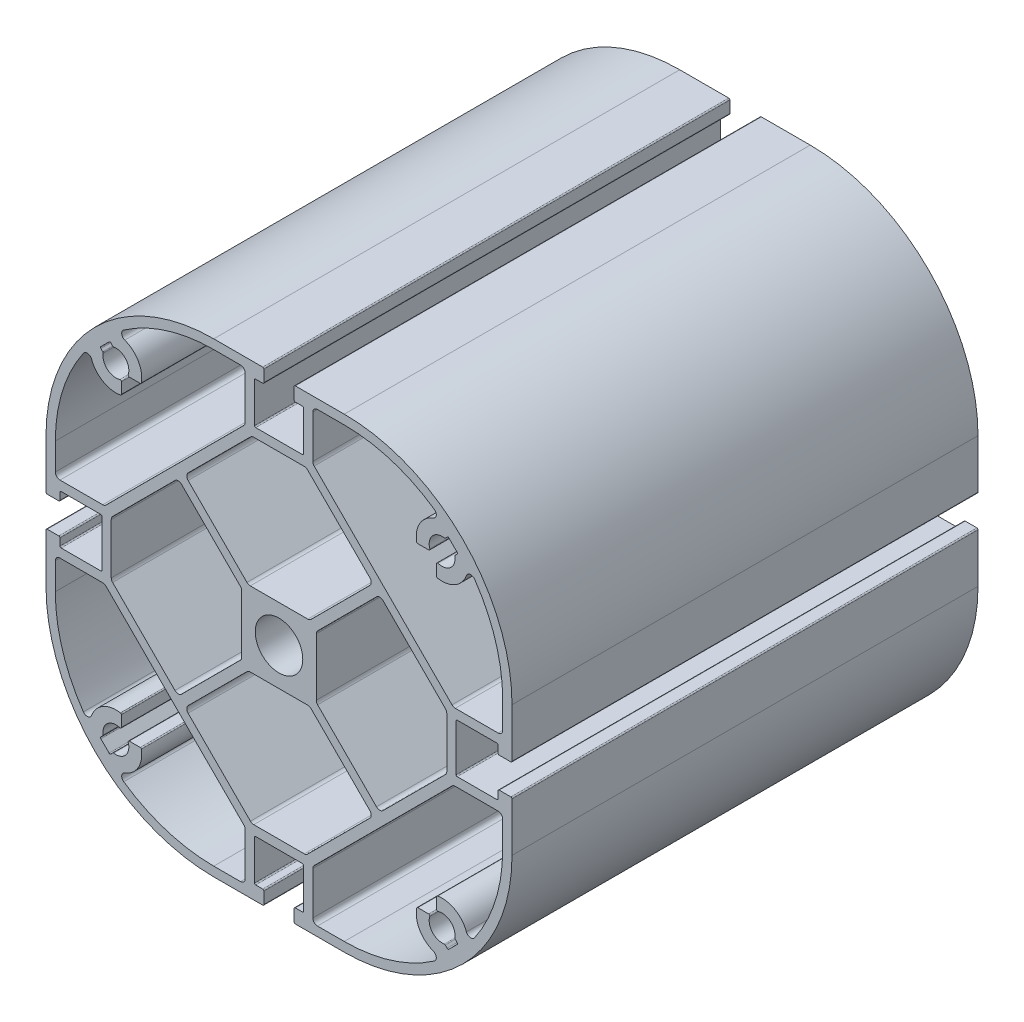
SolidWorks part; units mm, degrees
material "6061 Alaşım"
ref_plane "Ön Düzlem" through (0, 0, 0) normal (0, 0, 1) x (1, 0, 0)
ref_plane "Üst Düzlem" through (0, 0, 0) normal (0, 1, 0) x (1, 0, 0)
ref_plane "Sağ Düzlem" through (0, 0, 0) normal (1, 0, 0) x (0, 0, -1)
sketch "Çizim1" plane through (0, 0, 0) normal (0, 0, 1) x (1, 0, 0)
  line L0 (-50, 0) -> (50, 0) construction
  line L1 (50, -50) -> (-50, -50) construction
  line L2 (50, -50) -> (50, 50) construction
  line L3 (50, 50) -> (-50, 50) construction
  line L4 (-50, -50) -> (-50, 50) construction
  line L5 (50, -50) -> (-50, 50) construction
  line L6 (50, 50) -> (-50, -50) construction
  line L7 (0, 50) -> (0, -50) construction
  line L8 (3.25, 49.75) -> (3.25, 47.25)
  line L9 (3.5, 47) -> (5, 47)
  line L10 (5.25, 46.75) -> (5.25, 38.25)
  line L11 (5, 38) -> (0, 38)
  line L12 (37.1213, 7.5429) -> (7.5429, 37.1213)
  line L13 (7.25, 37.8284) -> (7.25, 47)
  line L14 (8.25, 48) -> (14, 48)
  line L15 (0, 36) -> (5.4216, 36)
  line L16 (6.1287, 35.7071) -> (19.5037, 22.3321)
  line L17 (19.5037, 20.9179) -> (6.8787, 8.2929)
  line L18 (6.1716, 8) -> (0, 8)
  line L19 (3.5, 50) -> (14, 50)
  line L20 (5.25, 38) -> (38, 5.25) construction
  line L21 (0, 8) -> (0, 5.1)
  line L22 (3.6062, 3.6062) -> (22.3321, 22.3321) construction
  line L23 (0, 38) -> (0, 36)
  line L24 (32.485, 33.8272) -> (35, 35) construction
  line L25 (35, 35) -> (33.8272, 32.485) construction
  line L26 (32.1192, 33.8272) -> (29.7809, 33.8272)
  line L28 (38.2184, 36.4506) -> (36.4506, 38.2184)
  line L29 (36.0971, 38.2184) -> (35.6841, 37.8054)
  line L30 (37.3345, 37.3345) -> (39.4558, 39.4558)
  line L31 (38.2184, 36.0971) -> (37.8054, 35.6841)
  line L32 (33.8272, 32.1192) -> (33.8272, 29.7809)
  line L33 (48, 8.25) -> (48, 14)
  line L34 (37.8284, 7.25) -> (47, 7.25)
  line L35 (8, 0) -> (5.1, 0)
  line L36 (8, 6.1716) -> (8, 0)
  line L37 (20.9179, 19.5037) -> (8.2929, 6.8787)
  line L38 (35.7071, 6.1287) -> (22.3321, 19.5037)
  line L39 (36, 0) -> (36, 5.4216)
  line L40 (38, 0) -> (36, 0)
  line L41 (38, 5) -> (38, 0)
  line L42 (46.75, 5.25) -> (38.25, 5.25)
  line L43 (47, 3.5) -> (47, 5)
  line L44 (49.75, 3.25) -> (47.25, 3.25)
  line L45 (50, 3.5) -> (50, 14)
  line L46 (0, -8) -> (0, -5.1)
  line L47 (6.1716, -8) -> (0, -8)
  line L48 (19.5037, -20.9179) -> (6.8787, -8.2929)
  line L49 (6.1287, -35.7071) -> (19.5037, -22.3321)
  line L50 (0, -36) -> (5.4216, -36)
  line L51 (0, -38) -> (0, -36)
  line L52 (5, -38) -> (0, -38)
  line L53 (5.25, -46.75) -> (5.25, -38.25)
  line L54 (3.5, -47) -> (5, -47)
  line L55 (3.25, -49.75) -> (3.25, -47.25)
  line L56 (3.5, -50) -> (14, -50)
  line L57 (50, -3.5) -> (50, -14)
  line L58 (49.75, -3.25) -> (47.25, -3.25)
  line L59 (47, -3.5) -> (47, -5)
  line L60 (46.75, -5.25) -> (38.25, -5.25)
  line L61 (38, -5) -> (38, 0)
  line L62 (38, 0) -> (36, 0)
  line L63 (36, 0) -> (36, -5.4216)
  line L64 (35.7071, -6.1287) -> (22.3321, -19.5037)
  line L65 (20.9179, -19.5037) -> (8.2929, -6.8787)
  line L66 (8, -6.1716) -> (8, 0)
  line L67 (8, 0) -> (5.1, 0)
  line L68 (36.4506, -38.2184) -> (38.2184, -36.4506)
  line L69 (38.2184, -36.0971) -> (37.8054, -35.6841)
  line L70 (33.8272, -32.1192) -> (33.8272, -29.7809)
  line L71 (48, -8.25) -> (48, -14)
  line L72 (37.8284, -7.25) -> (47, -7.25)
  line L73 (7.5429, -37.1213) -> (37.1213, -7.5429)
  line L74 (7.25, -37.8284) -> (7.25, -47)
  line L75 (8.25, -48) -> (14, -48)
  line L76 (32.1192, -33.8272) -> (29.7809, -33.8272)
  line L77 (36.0971, -38.2184) -> (35.6841, -37.8054)
  line L78 (-8, 0) -> (-5.1, 0)
  line L79 (-8, -6.1716) -> (-8, 0)
  line L80 (-20.9179, -19.5037) -> (-8.2929, -6.8787)
  line L81 (-35.7071, -6.1287) -> (-22.3321, -19.5037)
  line L82 (-36, 0) -> (-36, -5.4216)
  line L83 (-38, 0) -> (-36, 0)
  line L84 (-38, -5) -> (-38, 0)
  line L85 (-46.75, -5.25) -> (-38.25, -5.25)
  line L86 (-47, -3.5) -> (-47, -5)
  line L87 (-49.75, -3.25) -> (-47.25, -3.25)
  line L88 (-50, -3.5) -> (-50, -14)
  line L89 (-3.5, -50) -> (-14, -50)
  line L90 (-3.25, -49.75) -> (-3.25, -47.25)
  line L91 (-3.5, -47) -> (-5, -47)
  line L92 (-5.25, -46.75) -> (-5.25, -38.25)
  line L93 (-5, -38) -> (0, -38)
  line L94 (0, -38) -> (0, -36)
  line L95 (0, -36) -> (-5.4216, -36)
  line L96 (-6.1287, -35.7071) -> (-19.5037, -22.3321)
  line L97 (-19.5037, -20.9179) -> (-6.8787, -8.2929)
  line L98 (-6.1716, -8) -> (0, -8)
  line L99 (0, -8) -> (0, -5.1)
  line L100 (-38.2184, -36.4506) -> (-36.4506, -38.2184)
  line L101 (-36.0971, -38.2184) -> (-35.6841, -37.8054)
  line L102 (-32.1192, -33.8272) -> (-29.7809, -33.8272)
  line L103 (-8.25, -48) -> (-14, -48)
  line L104 (-7.25, -37.8284) -> (-7.25, -47)
  line L105 (-37.1213, -7.5429) -> (-7.5429, -37.1213)
  line L106 (-37.8284, -7.25) -> (-47, -7.25)
  line L107 (-48, -8.25) -> (-48, -14)
  line L108 (-33.8272, -32.1192) -> (-33.8272, -29.7809)
  line L109 (-38.2184, -36.0971) -> (-37.8054, -35.6841)
  line L110 (0, 8) -> (0, 5.1)
  line L111 (-6.1716, 8) -> (0, 8)
  line L112 (-19.5037, 20.9179) -> (-6.8787, 8.2929)
  line L113 (-6.1287, 35.7071) -> (-19.5037, 22.3321)
  line L114 (0, 36) -> (-5.4216, 36)
  line L115 (0, 38) -> (0, 36)
  line L116 (-5, 38) -> (0, 38)
  line L117 (-5.25, 46.75) -> (-5.25, 38.25)
  line L118 (-3.5, 47) -> (-5, 47)
  line L119 (-3.25, 49.75) -> (-3.25, 47.25)
  line L120 (-3.5, 50) -> (-14, 50)
  line L121 (-50, 3.5) -> (-50, 14)
  line L122 (-49.75, 3.25) -> (-47.25, 3.25)
  line L123 (-47, 3.5) -> (-47, 5)
  line L124 (-46.75, 5.25) -> (-38.25, 5.25)
  line L125 (-38, 5) -> (-38, 0)
  line L126 (-38, 0) -> (-36, 0)
  line L127 (-36, 0) -> (-36, 5.4216)
  line L128 (-35.7071, 6.1287) -> (-22.3321, 19.5037)
  line L129 (-20.9179, 19.5037) -> (-8.2929, 6.8787)
  line L130 (-8, 6.1716) -> (-8, 0)
  line L131 (-8, 0) -> (-5.1, 0)
  line L132 (-36.4506, 38.2184) -> (-38.2184, 36.4506)
  line L133 (-38.2184, 36.0971) -> (-37.8054, 35.6841)
  line L134 (-33.8272, 32.1192) -> (-33.8272, 29.7809)
  line L135 (-48, 8.25) -> (-48, 14)
  line L136 (-37.8284, 7.25) -> (-47, 7.25)
  line L137 (-7.5429, 37.1213) -> (-37.1213, 7.5429)
  line L138 (-7.25, 37.8284) -> (-7.25, 47)
  line L139 (-8.25, 48) -> (-14, 48)
  line L140 (-32.1192, 33.8272) -> (-29.7809, 33.8272)
  line L141 (-36.0971, 38.2184) -> (-35.6841, 37.8054)
  arc A1 (14, 50) -> (50, 14) centre (14, 14) cw
  arc A2 (14, 48) -> (38.0416, 38.0416) centre (14, 14) cw construction
  circle A3 centre (0, 0) radius 5.1 construction
  arc A4 (0, 5.1) -> (5.1, 0) centre (0, 0) cw
  circle A5 centre (35, 35) radius 2.775 construction
  circle A6 centre (35, 35) radius 5.55 construction
  arc A7 (14, 48) -> (33.3225, 41.9758) centre (14, 14) cw
  arc A8 (29.5348, 34.0337) -> (33.097, 40.2136) centre (35, 35) cw
  arc A9 (32.3573, 34.1535) -> (36.9622, 36.9622) centre (35, 35) cw construction
  arc A10 (5.25, 38.25) -> (5, 38) centre (5, 38.25) cw
  arc A11 (5, 47) -> (5.25, 46.75) centre (5, 46.75) cw
  arc A12 (3.25, 49.75) -> (3.5, 50) centre (3.5, 49.75) cw
  arc A13 (3.25, 47.25) -> (3.5, 47) centre (3.5, 47.25) ccw
  arc A14 (33.3225, 41.9758) -> (33.097, 40.2136) centre (32.7541, 41.1529) cw
  arc A15 (6.8787, 8.2929) -> (6.1716, 8) centre (6.1716, 9) cw
  arc A16 (19.5037, 22.3321) -> (19.5037, 20.9179) centre (18.7966, 21.625) cw
  arc A17 (5.4216, 36) -> (6.1287, 35.7071) centre (5.4216, 35) cw
  arc A18 (7.5429, 37.1213) -> (7.25, 37.8284) centre (8.25, 37.8284) cw
  arc A19 (7.25, 47) -> (8.25, 48) centre (8.25, 47) cw
  arc A20 (32.3573, 34.1535) -> (32.1192, 33.8272) centre (32.1192, 34.0772) cw
  arc A21 (29.7809, 33.8272) -> (29.5348, 34.0337) centre (29.7809, 34.0772) cw
  arc A22 (32.3573, 34.1535) -> (35.4654, 37.7357) centre (35, 35) cw
  arc A23 (36.4506, 38.2184) -> (36.0971, 38.2184) centre (36.2739, 38.0416) ccw
  arc A24 (35.6841, 37.8054) -> (35.4654, 37.7357) centre (35.5073, 37.9822) cw
  arc A25 (38.2184, 36.4506) -> (38.2184, 36.0971) centre (38.0416, 36.2739) cw
  arc A26 (37.8054, 35.6841) -> (37.7357, 35.4654) centre (37.9822, 35.5073) ccw
  arc A27 (34.1535, 32.3573) -> (37.7357, 35.4654) centre (35, 35) ccw
  arc A28 (34.1535, 32.3573) -> (33.8272, 32.1192) centre (34.0772, 32.1192) ccw
  arc A29 (33.8272, 29.7809) -> (34.0337, 29.5348) centre (34.0772, 29.7809) ccw
  arc A30 (34.0337, 29.5348) -> (40.2136, 33.097) centre (35, 35) ccw
  arc A31 (41.9758, 33.3225) -> (40.2136, 33.097) centre (41.1529, 32.7541) ccw
  arc A32 (48, 14) -> (41.9758, 33.3225) centre (14, 14) ccw
  arc A33 (47, 7.25) -> (48, 8.25) centre (47, 8.25) ccw
  arc A34 (37.1213, 7.5429) -> (37.8284, 7.25) centre (37.8284, 8.25) ccw
  arc A35 (8.2929, 6.8787) -> (8, 6.1716) centre (9, 6.1716) ccw
  arc A36 (22.3321, 19.5037) -> (20.9179, 19.5037) centre (21.625, 18.7966) ccw
  arc A37 (36, 5.4216) -> (35.7071, 6.1287) centre (35, 5.4216) ccw
  arc A38 (38.25, 5.25) -> (38, 5) centre (38.25, 5) ccw
  arc A39 (47, 5) -> (46.75, 5.25) centre (46.75, 5) ccw
  arc A40 (47.25, 3.25) -> (47, 3.5) centre (47.25, 3.5) cw
  arc A41 (49.75, 3.25) -> (50, 3.5) centre (49.75, 3.5) ccw
  arc A42 (5.1, 0) -> (0, -5.1) centre (0, 0) cw
  arc A43 (6.8787, -8.2929) -> (6.1716, -8) centre (6.1716, -9) ccw
  arc A44 (19.5037, -22.3321) -> (19.5037, -20.9179) centre (18.7966, -21.625) ccw
  arc A45 (5.4216, -36) -> (6.1287, -35.7071) centre (5.4216, -35) ccw
  arc A46 (5.25, -38.25) -> (5, -38) centre (5, -38.25) ccw
  arc A47 (5, -47) -> (5.25, -46.75) centre (5, -46.75) ccw
  arc A48 (3.25, -47.25) -> (3.5, -47) centre (3.5, -47.25) cw
  arc A49 (3.25, -49.75) -> (3.5, -50) centre (3.5, -49.75) ccw
  arc A50 (50, -14) -> (14, -50) centre (14, -14) cw
  arc A51 (49.75, -3.25) -> (50, -3.5) centre (49.75, -3.5) cw
  arc A52 (47.25, -3.25) -> (47, -3.5) centre (47.25, -3.5) ccw
  arc A53 (47, -5) -> (46.75, -5.25) centre (46.75, -5) cw
  arc A54 (38.25, -5.25) -> (38, -5) centre (38.25, -5) cw
  arc A55 (36, -5.4216) -> (35.7071, -6.1287) centre (35, -5.4216) cw
  arc A56 (22.3321, -19.5037) -> (20.9179, -19.5037) centre (21.625, -18.7966) cw
  arc A57 (8.2929, -6.8787) -> (8, -6.1716) centre (9, -6.1716) cw
  arc A58 (38.2184, -36.4506) -> (38.2184, -36.0971) centre (38.0416, -36.2739) ccw
  arc A59 (37.8054, -35.6841) -> (37.7357, -35.4654) centre (37.9822, -35.5073) cw
  arc A60 (34.1535, -32.3573) -> (37.7357, -35.4654) centre (35, -35) cw
  arc A61 (34.1535, -32.3573) -> (33.8272, -32.1192) centre (34.0772, -32.1192) cw
  arc A62 (33.8272, -29.7809) -> (34.0337, -29.5348) centre (34.0772, -29.7809) cw
  arc A63 (34.0337, -29.5348) -> (40.2136, -33.097) centre (35, -35) cw
  arc A64 (41.9758, -33.3225) -> (40.2136, -33.097) centre (41.1529, -32.7541) cw
  arc A65 (48, -14) -> (41.9758, -33.3225) centre (14, -14) cw
  arc A66 (47, -7.25) -> (48, -8.25) centre (47, -8.25) cw
  arc A67 (37.1213, -7.5429) -> (37.8284, -7.25) centre (37.8284, -8.25) cw
  arc A68 (7.5429, -37.1213) -> (7.25, -37.8284) centre (8.25, -37.8284) ccw
  arc A69 (7.25, -47) -> (8.25, -48) centre (8.25, -47) ccw
  arc A70 (14, -48) -> (33.3225, -41.9758) centre (14, -14) ccw
  arc A71 (33.3225, -41.9758) -> (33.097, -40.2136) centre (32.7541, -41.1529) ccw
  arc A72 (29.5348, -34.0337) -> (33.097, -40.2136) centre (35, -35) ccw
  arc A73 (29.7809, -33.8272) -> (29.5348, -34.0337) centre (29.7809, -34.0772) ccw
  arc A74 (32.3573, -34.1535) -> (32.1192, -33.8272) centre (32.1192, -34.0772) ccw
  arc A75 (32.3573, -34.1535) -> (35.4654, -37.7357) centre (35, -35) ccw
  arc A76 (35.6841, -37.8054) -> (35.4654, -37.7357) centre (35.5073, -37.9822) ccw
  arc A77 (36.4506, -38.2184) -> (36.0971, -38.2184) centre (36.2739, -38.0416) cw
  arc A78 (0, -5.1) -> (-5.1, 0) centre (0, 0) cw
  arc A79 (-8.2929, -6.8787) -> (-8, -6.1716) centre (-9, -6.1716) ccw
  arc A80 (-22.3321, -19.5037) -> (-20.9179, -19.5037) centre (-21.625, -18.7966) ccw
  arc A81 (-36, -5.4216) -> (-35.7071, -6.1287) centre (-35, -5.4216) ccw
  arc A82 (-38.25, -5.25) -> (-38, -5) centre (-38.25, -5) ccw
  arc A83 (-47, -5) -> (-46.75, -5.25) centre (-46.75, -5) ccw
  arc A84 (-47.25, -3.25) -> (-47, -3.5) centre (-47.25, -3.5) cw
  arc A85 (-49.75, -3.25) -> (-50, -3.5) centre (-49.75, -3.5) ccw
  arc A86 (-14, -50) -> (-50, -14) centre (-14, -14) cw
  arc A87 (-3.25, -49.75) -> (-3.5, -50) centre (-3.5, -49.75) cw
  arc A88 (-3.25, -47.25) -> (-3.5, -47) centre (-3.5, -47.25) ccw
  arc A89 (-5, -47) -> (-5.25, -46.75) centre (-5, -46.75) cw
  arc A90 (-5.25, -38.25) -> (-5, -38) centre (-5, -38.25) cw
  arc A91 (-5.4216, -36) -> (-6.1287, -35.7071) centre (-5.4216, -35) cw
  arc A92 (-19.5037, -22.3321) -> (-19.5037, -20.9179) centre (-18.7966, -21.625) cw
  arc A93 (-6.8787, -8.2929) -> (-6.1716, -8) centre (-6.1716, -9) cw
  arc A94 (-36.4506, -38.2184) -> (-36.0971, -38.2184) centre (-36.2739, -38.0416) ccw
  arc A95 (-35.6841, -37.8054) -> (-35.4654, -37.7357) centre (-35.5073, -37.9822) cw
  arc A96 (-32.3573, -34.1535) -> (-35.4654, -37.7357) centre (-35, -35) cw
  arc A97 (-32.3573, -34.1535) -> (-32.1192, -33.8272) centre (-32.1192, -34.0772) cw
  arc A98 (-29.7809, -33.8272) -> (-29.5348, -34.0337) centre (-29.7809, -34.0772) cw
  arc A99 (-29.5348, -34.0337) -> (-33.097, -40.2136) centre (-35, -35) cw
  arc A100 (-33.3225, -41.9758) -> (-33.097, -40.2136) centre (-32.7541, -41.1529) cw
  arc A101 (-14, -48) -> (-33.3225, -41.9758) centre (-14, -14) cw
  arc A102 (-7.25, -47) -> (-8.25, -48) centre (-8.25, -47) cw
  arc A103 (-7.5429, -37.1213) -> (-7.25, -37.8284) centre (-8.25, -37.8284) cw
  arc A104 (-37.1213, -7.5429) -> (-37.8284, -7.25) centre (-37.8284, -8.25) ccw
  arc A105 (-47, -7.25) -> (-48, -8.25) centre (-47, -8.25) ccw
  arc A106 (-48, -14) -> (-41.9758, -33.3225) centre (-14, -14) ccw
  arc A107 (-41.9758, -33.3225) -> (-40.2136, -33.097) centre (-41.1529, -32.7541) ccw
  arc A108 (-34.0337, -29.5348) -> (-40.2136, -33.097) centre (-35, -35) ccw
  arc A109 (-33.8272, -29.7809) -> (-34.0337, -29.5348) centre (-34.0772, -29.7809) ccw
  arc A110 (-34.1535, -32.3573) -> (-33.8272, -32.1192) centre (-34.0772, -32.1192) ccw
  arc A111 (-34.1535, -32.3573) -> (-37.7357, -35.4654) centre (-35, -35) ccw
  arc A112 (-37.8054, -35.6841) -> (-37.7357, -35.4654) centre (-37.9822, -35.5073) ccw
  arc A113 (-38.2184, -36.4506) -> (-38.2184, -36.0971) centre (-38.0416, -36.2739) cw
  arc A114 (-5.1, 0) -> (0, 5.1) centre (0, 0) cw
  arc A115 (-6.8787, 8.2929) -> (-6.1716, 8) centre (-6.1716, 9) ccw
  arc A116 (-19.5037, 22.3321) -> (-19.5037, 20.9179) centre (-18.7966, 21.625) ccw
  arc A117 (-5.4216, 36) -> (-6.1287, 35.7071) centre (-5.4216, 35) ccw
  arc A118 (-5.25, 38.25) -> (-5, 38) centre (-5, 38.25) ccw
  arc A119 (-5, 47) -> (-5.25, 46.75) centre (-5, 46.75) ccw
  arc A120 (-3.25, 47.25) -> (-3.5, 47) centre (-3.5, 47.25) cw
  arc A121 (-3.25, 49.75) -> (-3.5, 50) centre (-3.5, 49.75) ccw
  arc A122 (-50, 14) -> (-14, 50) centre (-14, 14) cw
  arc A123 (-49.75, 3.25) -> (-50, 3.5) centre (-49.75, 3.5) cw
  arc A124 (-47.25, 3.25) -> (-47, 3.5) centre (-47.25, 3.5) ccw
  arc A125 (-47, 5) -> (-46.75, 5.25) centre (-46.75, 5) cw
  arc A126 (-38.25, 5.25) -> (-38, 5) centre (-38.25, 5) cw
  arc A127 (-36, 5.4216) -> (-35.7071, 6.1287) centre (-35, 5.4216) cw
  arc A128 (-22.3321, 19.5037) -> (-20.9179, 19.5037) centre (-21.625, 18.7966) cw
  arc A129 (-8.2929, 6.8787) -> (-8, 6.1716) centre (-9, 6.1716) cw
  arc A130 (-38.2184, 36.4506) -> (-38.2184, 36.0971) centre (-38.0416, 36.2739) ccw
  arc A131 (-37.8054, 35.6841) -> (-37.7357, 35.4654) centre (-37.9822, 35.5073) cw
  arc A132 (-34.1535, 32.3573) -> (-37.7357, 35.4654) centre (-35, 35) cw
  arc A133 (-34.1535, 32.3573) -> (-33.8272, 32.1192) centre (-34.0772, 32.1192) cw
  arc A134 (-33.8272, 29.7809) -> (-34.0337, 29.5348) centre (-34.0772, 29.7809) cw
  arc A135 (-34.0337, 29.5348) -> (-40.2136, 33.097) centre (-35, 35) cw
  arc A136 (-41.9758, 33.3225) -> (-40.2136, 33.097) centre (-41.1529, 32.7541) cw
  arc A137 (-48, 14) -> (-41.9758, 33.3225) centre (-14, 14) cw
  arc A138 (-47, 7.25) -> (-48, 8.25) centre (-47, 8.25) cw
  arc A139 (-37.1213, 7.5429) -> (-37.8284, 7.25) centre (-37.8284, 8.25) cw
  arc A140 (-7.5429, 37.1213) -> (-7.25, 37.8284) centre (-8.25, 37.8284) ccw
  arc A141 (-7.25, 47) -> (-8.25, 48) centre (-8.25, 47) ccw
  arc A142 (-14, 48) -> (-33.3225, 41.9758) centre (-14, 14) ccw
  arc A143 (-33.3225, 41.9758) -> (-33.097, 40.2136) centre (-32.7541, 41.1529) ccw
  arc A144 (-29.5348, 34.0337) -> (-33.097, 40.2136) centre (-35, 35) ccw
  arc A145 (-29.7809, 33.8272) -> (-29.5348, 34.0337) centre (-29.7809, 34.0772) ccw
  arc A146 (-32.3573, 34.1535) -> (-32.1192, 33.8272) centre (-32.1192, 34.0772) ccw
  arc A147 (-32.3573, 34.1535) -> (-35.4654, 37.7357) centre (-35, 35) ccw
  arc A148 (-35.6841, 37.8054) -> (-35.4654, 37.7357) centre (-35.5073, 37.9822) ccw
  arc A149 (-36.4506, 38.2184) -> (-36.0971, 38.2184) centre (-36.2739, 38.0416) cw
  point P0 (0, 0)
  point P53 (3.25, 50)
  point P56 (3.25, 47)
  point P59 (35.2459, 40.5446)
  point P75 (29.5753, 33.8272)
  point P84 (35.5902, 37.7115)
  point P86 (21.625, 21.625)
  point P437 (0, 0)
  dimension "D8" = 36
  dimension "D15" = 10.2
  dimension "D17" = 11.1
  dimension "D18" = 5.55
  dimension "D21" = 0.25
  dimension "D22" = 1
  dimension "D23" = 0.25
  dimension "D26" = 0.25
  dimension "D1" = 100
  dimension "D2" = 100
  dimension "D3" = 6.5
  dimension "D4" = 10.5
  dimension "D5" = 3
  dimension "D6" = 2
  dimension "D7" = 12
  dimension "D9" = 2
  dimension "D10" = 2
  dimension "D11" = 2
  dimension "D12" = 2
  dimension "D13" = 1
  dimension "D14" = 8
  dimension "D16" = 35
  dimension "D19" = 20
  dimension "D20" = 160
  dimension "D24" = 4
  dimension "D25" = 1.5
extrude "Yükseklik-Ekstrüzyon1" add sketch "Çizim1" against normal blind 100
